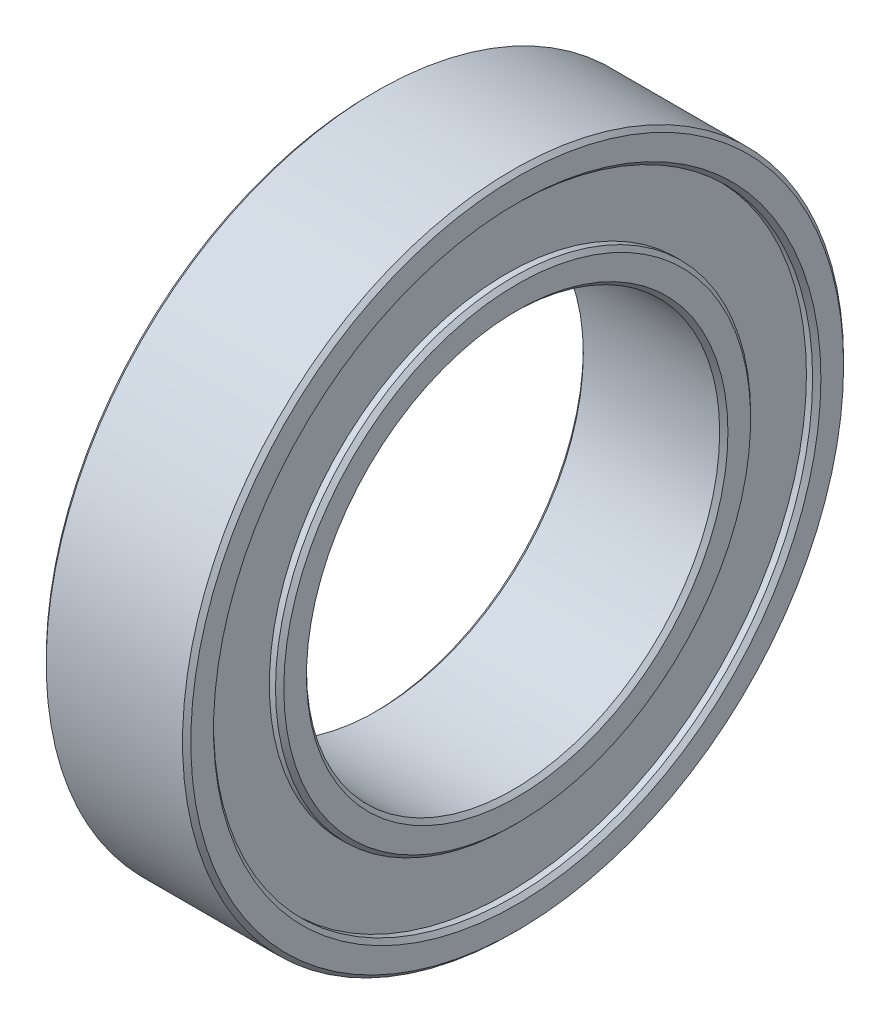
SolidWorks part; units mm, degrees
ref_plane "Front Plane" through (0, 0, 0) normal (0, 0, 1) x (1, 0, 0)
ref_plane "Top Plane" through (0, 0, 0) normal (0, 1, 0) x (1, 0, 0)
ref_plane "Right Plane" through (0, 0, 0) normal (1, 0, 0) x (0, 0, -1)
sketch "Sketch1" plane through (0, 0, 0) normal (1, 0, 0) x (0, 0, -1)
  circle A0 centre (0, 0) radius 16
  circle A1 centre (0, 0) radius 10
  dimension "D1" = 20
  dimension "D2" = 32
extrude "Boss-Extrude1" add sketch "Sketch1" along normal mid plane 7
sketch "Sketch2" plane through (3.5, 0, 0) normal (1, 0, 0) x (0, 0, -1)
  line L0 (0, 14.5) -> (0, 16) construction
  line L1 (0, 11.5) -> (0, 10) construction
  circle A0 centre (0, 0) radius 14.5
  circle A1 centre (0, 0) radius 11.5
  circle A2 centre (0, 0) radius 16 construction
  circle A3 centre (0, 0) radius 10 construction
  dimension "D1" = 1.5
extrude "Cut-Extrude1" cut sketch "Sketch2" against normal blind 0.5
mirror "Mirror1" about plane through (0, 0, 0) normal (1, 0, 0) of "Cut-Extrude1"
chamfer "Chamfer1" distance 0.2 angle 45 8 edges at (-3.5, 0, -11.5) (-3.5, 0, -10) (-3.5, 0, -16) (-3.5, 0, -14.5) (3.5, 0, -11.5) (3.5, 0, -10) (3.5, 0, -16) (3.5, 0, -14.5)
